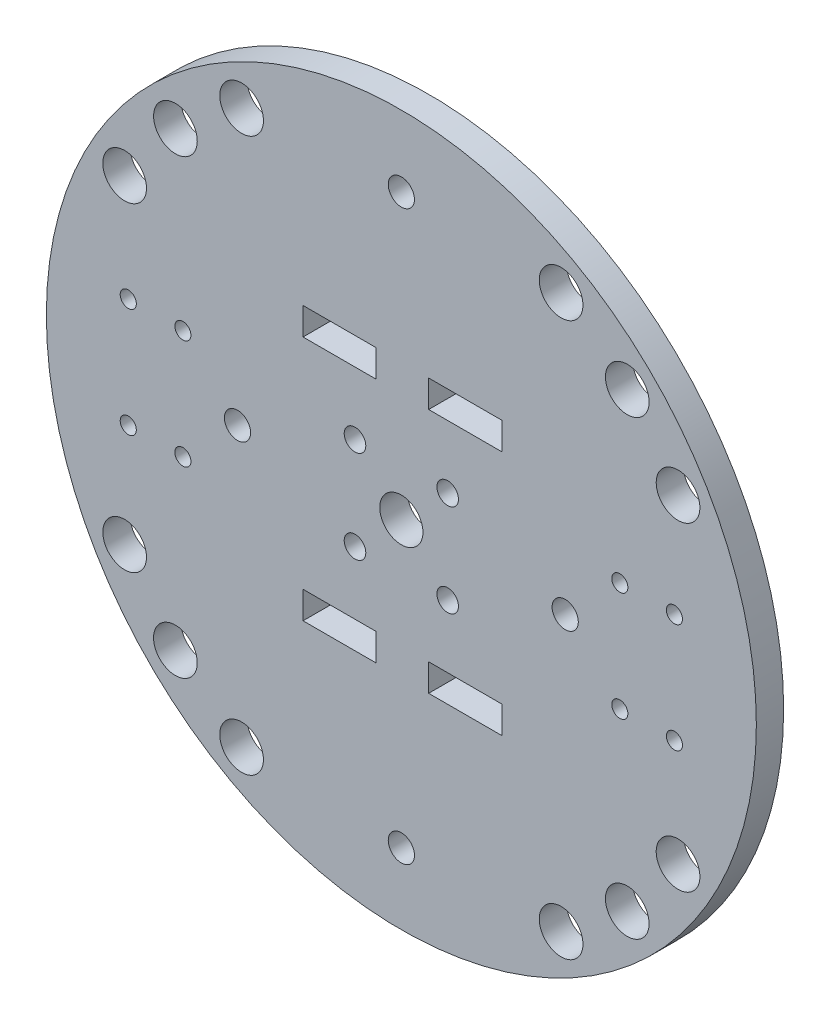
SolidWorks part; units mm, degrees
ref_plane "Front Plane" through (0, 0, 0) normal (0, 0, 1) x (1, 0, 0)
ref_plane "Top Plane" through (0, 0, 0) normal (0, 1, 0) x (1, 0, 0)
ref_plane "Right Plane" through (0, 0, 0) normal (1, 0, 0) x (0, 0, -1)
sketch "Sketch1" plane through (0, 0, 0) normal (0, 0, 1) x (1, 0, 0)
  line L1 (0, 0) -> (-65, 0) construction
  line L2 (18.4, 25) -> (18.4, 20)
  line L3 (-18, 25) -> (-4.6, 25)
  line L4 (-18, 25) -> (-18, 20)
  line L5 (-18, 20) -> (-4.6, 20)
  line L6 (-4.6, 25) -> (-4.6, 20)
  line L7 (18.4, 20) -> (5, 20)
  line L8 (5, 25) -> (5, 20)
  line L9 (18.4, 25) -> (5, 25)
  line L10 (5, -25) -> (5, -20)
  line L11 (18.4, -20) -> (5, -20)
  line L12 (18.4, -25) -> (18.4, -20)
  line L13 (18.4, -25) -> (5, -25)
  line L14 (-18, -25) -> (-18, -20)
  line L15 (-18, -25) -> (-4.6, -25)
  line L16 (-4.6, -25) -> (-4.6, -20)
  line L17 (-18, -20) -> (-4.6, -20)
  line L18 (0, 0) -> (-45.9619, 45.9619) construction
  line L19 (0, 0) -> (-32.5, 56.2917) construction
  line L20 (0, 0) -> (-56.2917, 32.5) construction
  circle A0 centre (0, 0) radius 65
  circle A1 centre (0, 0) radius 3.95
  circle A2 centre (0, 52) radius 2.4
  circle A3 centre (-30, 0) radius 2.4
  circle A4 centre (0, -52) radius 2.4
  circle A5 centre (30, 0) radius 2.4
  circle A6 centre (-41.3657, 41.3657) radius 4
  circle A7 centre (-29.25, 50.6625) radius 4
  circle A8 centre (-50.6625, 29.25) radius 4
  circle A9 centre (50.6625, 29.25) radius 4
  circle A10 centre (41.3657, 41.3657) radius 4
  circle A11 centre (29.25, 50.6625) radius 4
  circle A12 centre (50.6625, -29.25) radius 4
  circle A13 centre (41.3657, -41.3657) radius 4
  circle A14 centre (29.25, -50.6625) radius 4
  circle A15 centre (-29.25, -50.6625) radius 4
  circle A16 centre (-41.3657, -41.3657) radius 4
  circle A17 centre (-50.6625, -29.25) radius 4
  circle A18 centre (-40, 10) radius 1.475
  circle A19 centre (-50, 10) radius 1.475
  circle A20 centre (-40, -10) radius 1.475
  circle A21 centre (-50, -10) radius 1.475
  circle A22 centre (50, -10) radius 1.475
  circle A23 centre (40, -10) radius 1.475
  circle A24 centre (40, 10) radius 1.475
  circle A25 centre (50, 10) radius 1.475
  circle A26 centre (-8.4853, 8.4853) radius 1.975
  circle A27 centre (8.4853, 8.4853) radius 1.975
  circle A28 centre (8.4853, -8.4853) radius 1.975
  circle A29 centre (-8.4853, -8.4853) radius 1.975
  point P84 (0, 0)
  dimension "D1" = 130
  dimension "D2" = 7.9
  dimension "D3" = 4.8
  dimension "D5" = 4.8
  dimension "D12" = 8
  dimension "D16" = 8
  dimension "D18" = 8
  dimension "D20" = 2.95
  dimension "D23" = 2.95
  dimension "D26" = 3.95
  dimension "D4" = 52
  dimension "D6" = 30
  dimension "D7" = 18
  dimension "D8" = 13.4
  dimension "D9" = 5
  dimension "D10" = 20
  dimension "D11" = 45
  dimension "D13" = 58.5
  dimension "D14" = 15
  dimension "D15" = 15
  dimension "D17" = 58.5
  dimension "D19" = 58.5
  dimension "D21" = 18
  dimension "D22" = 10
  dimension "D24" = 10
  dimension "D25" = 10
  dimension "D27" = 12
  dimension "D28" = 4
  dimension "D29" = 20
extrude "Boss-Extrude1" add sketch "Sketch1" along normal blind 5
